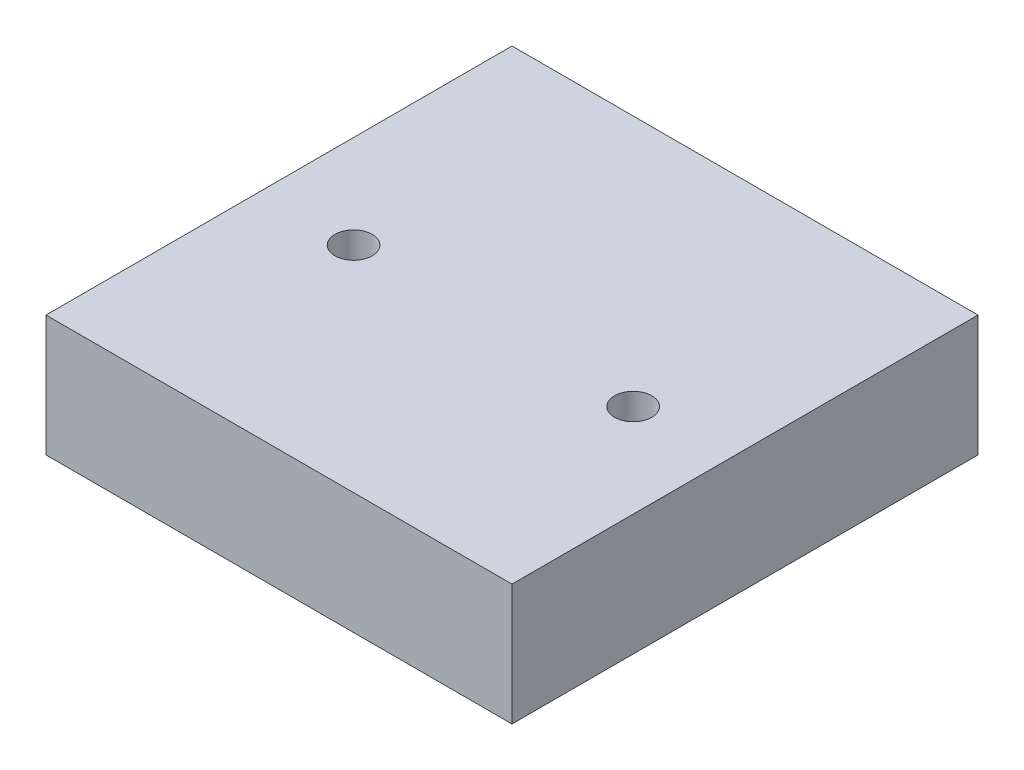
SolidWorks part; units mm, degrees
ref_plane "前视基准面" through (0, 0, 0) normal (0, 0, 1) x (1, 0, 0)
ref_plane "上视基准面" through (0, 0, 0) normal (0, 1, 0) x (1, 0, 0)
ref_plane "右视基准面" through (0, 0, 0) normal (1, 0, 0) x (0, 0, -1)
sketch "草图1" plane through (0, 0, 0) normal (0, 1, 0) x (1, 0, 0)
  line L1 (-25, -25) -> (25, -25)
  line L2 (-25, -25) -> (-25, 25)
  line L3 (-25, 25) -> (25, 25)
  line L4 (25, -25) -> (25, 25)
  line L5 (-25, -25) -> (25, 25) construction
  line L6 (-25, 25) -> (25, -25) construction
  point P0 (0, 0)
  dimension "D1" = 50
  dimension "D2" = 50
extrude "凸台-拉伸1" add sketch "草图1" along normal blind 13
sketch "草图3" plane through (0, 13, 0) normal (0, 1, 0) x (1, 0, 0)
  line L0 (-25, -2) -> (25, -2) construction
  line L1 (-25, 25) -> (-25, -25) construction
  line L2 (25, -25) -> (25, 25) construction
  line L3 (25, 25) -> (-25, 25) construction
  circle A0 centre (-15, -2) radius 2
  circle A1 centre (15, -2) radius 2
  point P15 (17.8124, -2.2733)
  dimension "D2" = 4
  dimension "D3" = 4
  dimension "D1" = 27
  dimension "D4" = 15
  dimension "D5" = 15
extrude "切除-拉伸1" cut sketch "草图3" against normal up to next
